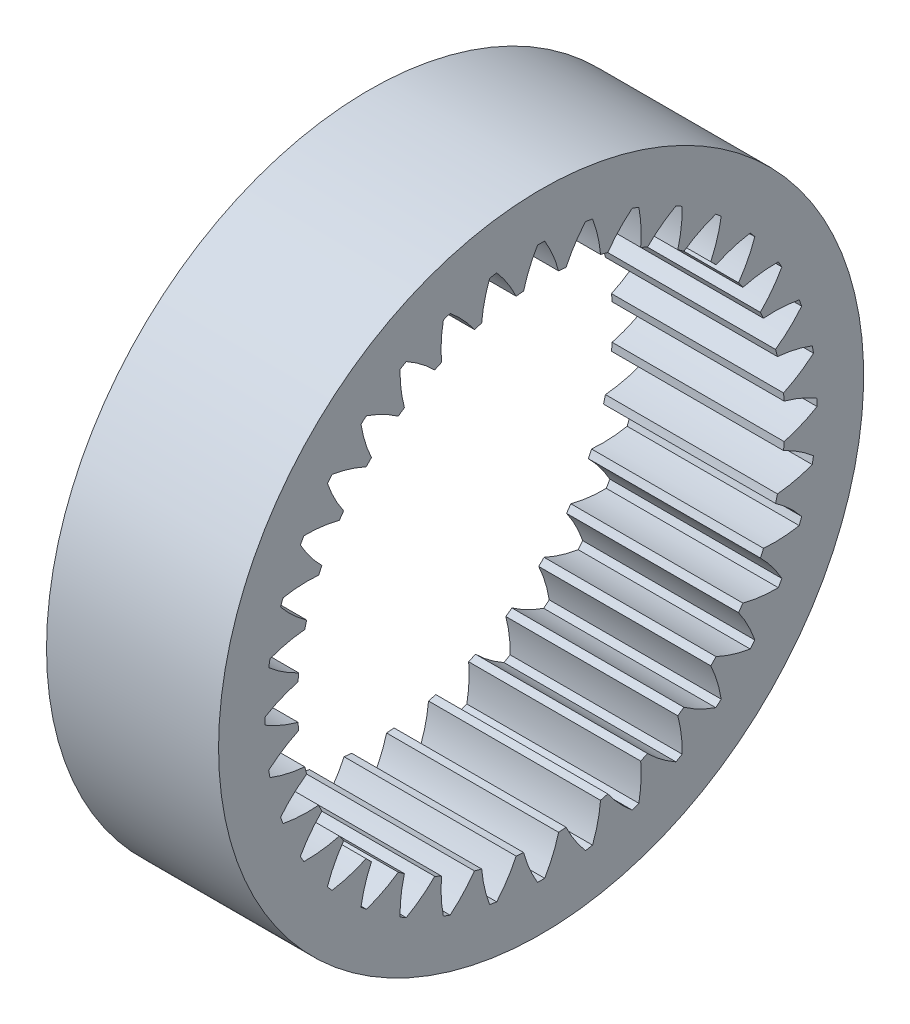
SolidWorks part; units mm, degrees
ref_plane "Plane1" through (0, 0, 0) normal (0, 0, 1) x (1, 0, 0)
ref_plane "Plane2" through (0, 0, 0) normal (0, 1, 0) x (1, 0, 0)
ref_plane "Plane3" through (0, 0, 0) normal (1, 0, 0) x (0, 0, -1)
sketch "HoldingSke" plane through (0, 0, 0) normal (0, 1, 0) x (1, 0, 0)
  line L0 (0, 0) -> (0.809, -0.5878)
  line L1 (-15, 0) -> (100, 0) construction
  line L2 (0, 0) -> (-2.1039, 2.3779)
  line L3 (0, 0) -> (-11.863, 4.5341)
  line L4 (0, 0) -> (6.9867, 5.0761)
  line L5 (0, 0) -> (-23.7986, -8.8762)
  line L6 (0, 0) -> (-10.5278, -7.1032)
  line L7 (-2.1039, 2.3779) -> (3.3635, 27.1825)
  line L8 (-76.2, 3.3779) -> (-54.61, 3.3779)
  line L9 (-71.009, 38.7566) -> (-53.1078, 45.2721)
  line L10 (-76.2, 71.12) -> (104.1128, 71.12)
  line L11 (0, 0) -> (-12, 0)
  line L12 (-76.2, 101.6) -> (-76.162, 101.6)
  line L13 (24.9733, 27.94) -> (52.9518, 28.4284)
  line L14 (24.9733, 27.94) -> (24.9743, 27.94)
  line L15 (24.9733, 27.94) -> (100.4006, 29.5858)
  circle A0 centre (0, 0) radius 22.5
  circle A1 centre (0, 0) radius 12.7
  circle A2 centre (0, 0) radius 12.7
  dimension "MHD" = 25.4
  dimension "Hub_dia" = 25.4
  dimension "Diameter" = 45
  dimension "Num_teeth" = 36
  dimension "Pitch" = 1
  dimension "Overall_len" = 25.4
  dimension "Show_teeth" = 36
  dimension "Thickness" = 12.7
  dimension "OAL" = 25.4001
  dimension "T_dim" = 21.59
  dimension "Ap" = 20
  dimension "H" = 19.05
  dimension "Pitch_radius" = 180.3128
  dimension "Width" = 12
  dimension "Backlash" = 0.038
  dimension "Addendum_fac" = 1
  dimension "Dedendum_fac" = 1.25
  dimension "Clearance_fac" = 0.25
  dimension "Dedendum_add" = 0.001
  dimension "Module" = 1
sketch "BasProSke" plane through (0, 0, 0) normal (0, 1, 0) x (1, 0, 0)
  line L0 (-10, 0) -> (60, 0) construction
  line L1 (0, 17) -> (0, 22.5)
  line L2 (0, 17) -> (12, 17)
  line L3 (12, 17) -> (12, 22.5)
  line L4 (12, 22.5) -> (0, 22.5)
  dimension "Diameter" = 45
  dimension "Thickness" = 12
  dimension "Inside_diameter" = 34
revolve "Base-Revolve" add sketch "BasProSke" angle 360 about L0
sketch "TooCutSke" plane through (0, 0, 0) normal (1, 0, 0) x (0, 0, -1)
  line L3 (0.8801, 17.9785) -> (0.8801, 53.6633) construction
  line L4 (0, 0) -> (0, 59.563) construction
  line L5 (0, 0) -> (-5.9551, 68.0675) construction
  line L6 (-7.4727, 14.6274) -> (36.372, 18.4633) construction
  circle A0 centre (0, 0) radius 18 construction
  circle A1 centre (0, 0) radius 19.251 construction
  circle A2 centre (0, 0) radius 15.223 construction
  circle A3 centre (0, 0) radius 16.9746 construction
  arc A4 (1.2277, 16.9301) -> (0.2498, 19.2494) centre (-7.4727, 14.6274) ccw
  arc A5 (1.2277, 16.9301) -> (-1.2277, 16.9301) centre (0, 0) ccw
  arc A6 (0.2498, 19.2494) -> (-0.2498, 19.2494) centre (0, 0) ccw
  arc A7 (-0.2498, 19.2494) -> (-1.2277, 16.9301) centre (7.4727, 14.6274) ccw
  dimension "Pitch_dia" = 36
  dimension "Base_dia" = 30.446
  dimension "Root_dia" = 38.502
  dimension "Overcut_dia" = 33.9492
  dimension "Flank_rad" = 9
  dimension "Half_ang" = 5
  dimension "Half_CT" = 0.8801
extrude "ToothCut" cut sketch "TooCutSke" along normal through all
fillet "Breaks" [suppressed] radius 0.1
fillet "RootFillets" [suppressed] radius 0.251
pattern_circular "TeethCuts" count 36 every 10 about axis through (-10, 0, 0) along (1, 0, 0) of "RootFillets", "Breaks", "ToothCut"
equation "' \"Module@HoldingSke\" = 6.35"
equation "' \"Num_teeth@HoldingSke\" = 24"
equation "' \"Ap@HoldingSke\" =  14.5"
equation "' \"Ap@HoldingSke\" = 14.5"
equation "' \"Width@HoldingSke\" = 12"
equation "' \"Diameter@HoldingSke\" = 8 * 25.4"
equation "' \"Show_teeth@HoldingSke\" = 100"
equation "' \"Backlash@HoldingSke\" = 0.009 * 25.4"
equation "' \"Addendum_fac@HoldingSke\" = 1.0"
equation "' \"Dedendum_fac@HoldingSke\" = 1.25"
equation "' \"Dedendum_add@HoldingSke\" = 0.00005 * 25.4"
equation "' \"Clearance_fac@HoldingSke\" = 0.25"
equation "\"Pitch@HoldingSke\" = 1 / \"Module@HoldingSke\" "
equation "\"Overcut_dia@TooCutSke\" = (\"Num_teeth@HoldingSke\" - 2 * \"Addendum_fac@HoldingSke\") / \"Pitch@HoldingSke\" - 0.002 * 25.4"
equation "\"Pitch_dia@TooCutSke\" = \"Num_teeth@HoldingSke\" / \"Pitch@HoldingSke\""
equation "\"Base_dia@TooCutSke\" = \"Num_teeth@HoldingSke\" / \"Pitch@HoldingSke\" * cos((\"Ap@HoldingSke\"  * 3.14159265 / 180)) * 0.90"
equation "\"Root_dia@TooCutSke\" = \"Num_teeth@HoldingSke\"  / \"Pitch@HoldingSke\" + 2 *  \"Dedendum_fac@HoldingSke\"/ \"Pitch@HoldingSke\" + \"Dedendum_add@HoldingSke\" * 2"
equation "\"Half_ang@TooCutSke\" = 180 / \"Num_teeth@HoldingSke\""
equation "\"Half_CT@TooCutSke\" = \"Num_teeth@HoldingSke\" / \"Pitch@HoldingSke\" * sin((3.14159265 / 2 / \"Num_teeth@HoldingSke\")) / 2 + 10 * \"Backlash@HoldingSke\" / 4"
equation "\"Flank_rad@TooCutSke\" = \"Num_teeth@HoldingSke\" / \"Pitch@HoldingSke\" / 4"
equation "\"Radius@RootFillets\"= \"Clearance_fac@HoldingSke\" / \"Pitch@HoldingSke\" + \"Dedendum_add@HoldingSke\""
equation "\"Break_rad@Breaks\" = 0.02 / \"Pitch@HoldingSke\" * 5"
equation "\"Num_teeth@TeethCuts\" = int( \"Show_teeth@HoldingSke\" ) + 1"
equation "\"Num_teeth@TeethCuts\" = ((sgn( \"Num_teeth@TeethCuts\" - \"Num_teeth@HoldingSke\" )-1)*( \"Num_teeth@TeethCuts\" - \"Num_teeth@HoldingSke\" ))/-2+ \"Num_teeth@HoldingSke\""
equation "\"Num_teeth@TeethCuts\" = ((sgn( \"Num_teeth@TeethCuts\" - 2.0)+1)*( \"Num_teeth@TeethCuts\" - 2.0))/2 +2.0"
equation "\"Angle@TeethCuts\" = 360.0 / \"Num_teeth@HoldingSke\""
equation "\"Diameter@BasProSke\" = \"Num_teeth@HoldingSke\"  / \"Pitch@HoldingSke\" + 2 *  \"Dedendum_fac@HoldingSke\"/ \"Pitch@HoldingSke\" + \"Dedendum_add@HoldingSke\" * 2 + 0.002 * 25.4"
equation "\"Diameter@BasProSke\" = ((sgn( \"Diameter@BasProSke\"  - \"Diameter@HoldingSke\" )+1)*( \"Diameter@BasProSke\"  - \"Diameter@HoldingSke\" ))/2 + \"Diameter@HoldingSke\""
equation "\"Inside_diameter@BasProSke\" =  (\"Num_teeth@HoldingSke\" - 2 * \"Addendum_fac@HoldingSke\") / \"Pitch@HoldingSke\" "
equation "\"Thickness@BasProSke\"  = \"Width@HoldingSke\""
